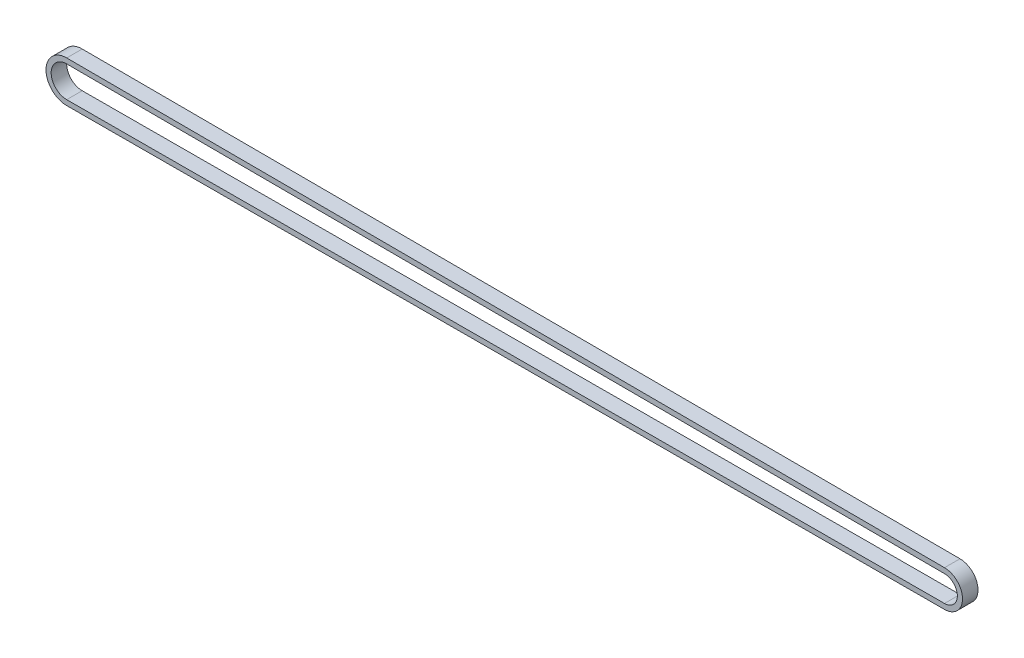
SolidWorks part; units mm, degrees
ref_plane "Plano frontal" through (0, 0, 0) normal (0, 0, 1) x (1, 0, 0)
ref_plane "Plano superior" through (0, 0, 0) normal (0, 1, 0) x (1, 0, 0)
ref_plane "Plano direito" through (0, 0, 0) normal (1, 0, 0) x (0, 0, -1)
sketch "Esboço1" plane through (0, 0, 0) normal (0, 0, 1) x (1, 0, 0)
  line L0 (0, 0) -> (-340, 0) construction
  line L1 (-339.9824, 6) -> (0.0147, 5)
  line L2 (-339.9824, -6) -> (0.0147, -5)
  line L3 (-339.9765, 8) -> (0.0206, 7)
  line L4 (-339.9765, -8) -> (0.0206, -7)
  arc A0 (0.0147, 5) -> (0.0147, -5) centre (0, 0) cw
  arc A1 (-339.9824, 6) -> (-339.9824, -6) centre (-340, 0) ccw
  arc A2 (0.0206, 7) -> (0.0206, -7) centre (0, 0) cw
  arc A3 (-339.9765, 8) -> (-339.9765, -8) centre (-340, 0) ccw
  dimension "D1" = 6
  dimension "D2" = 5
  dimension "D3" = 340
  dimension "D4" = 2
extrude "Ressalto-extrusão1" add sketch "Esboço1" along normal blind 6
